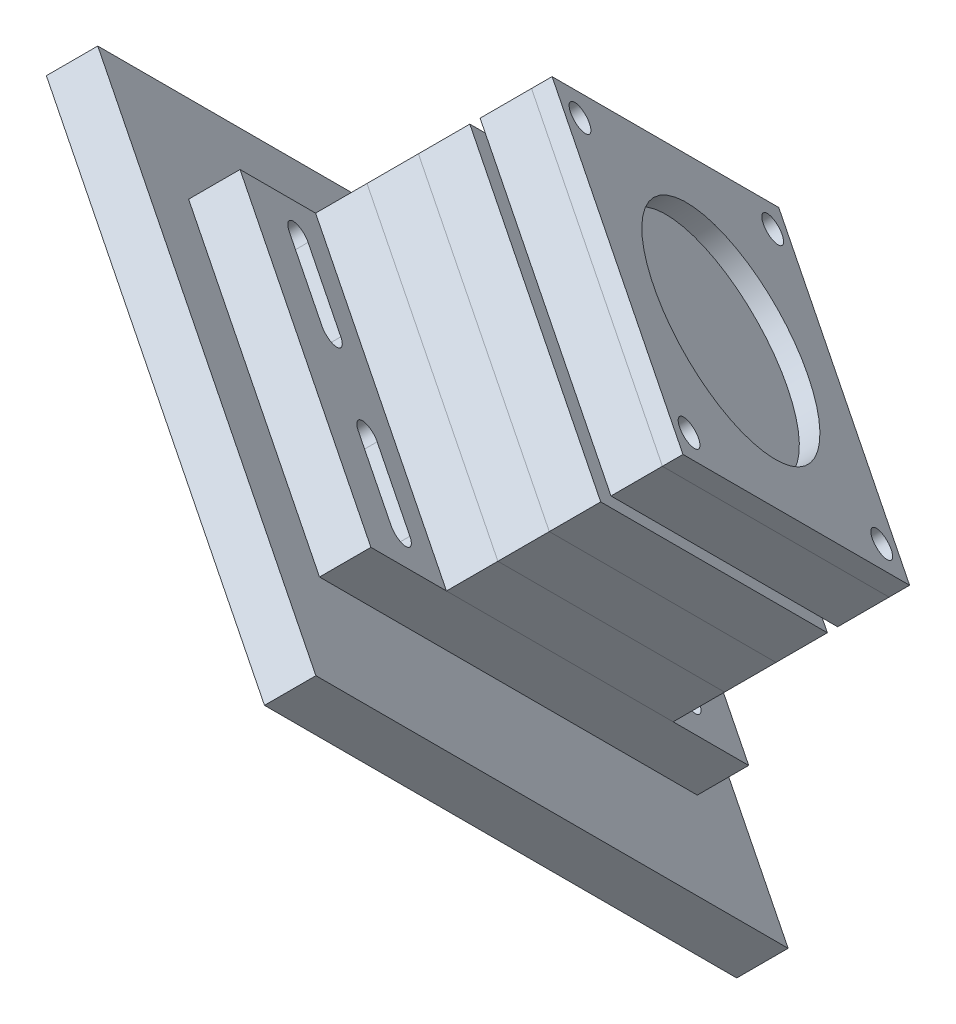
SolidWorks part; units mm, degrees
ref_plane "Front Plane" through (0, 0, 0) normal (0, 0, 1) x (1, 0, 0)
ref_plane "Top Plane" through (0, 0, 0) normal (0, 1, 0) x (1, 0, 0)
ref_plane "Right Plane" through (0, 0, 0) normal (1, 0, 0) x (0, 0, -1)
sketch "Sketch1" plane through (0, 0, 0) normal (0, 1, 0) x (1, 0, 0)
  line L1 (0, 0) -> (80, 0)
  line L2 (0, 0) -> (0, 80)
  line L3 (0, 80) -> (80, 80)
  line L4 (80, 0) -> (80, 80)
  dimension "D1" = 80
  dimension "D2" = 80
extrude "Boss-Extrude1" add sketch "Sketch1" along normal blind 80
sketch3d "3DSketch1"
  line L0 (0, 80, 0) -> (80, 0, 0)
  line L1 (80, 0, 0) -> (0, 0, -80)
  line L2 (0, 0, -80) -> (0, 80, 0)
ref_plane "Plane1" through (26.6667, 26.6667, -26.6667) normal (0.5774, 0.5774, -0.5774) x (-0.8165, 0.4082, -0.4082)
sketch "Sketch2" plane through (26.6667, 26.6667, -26.6667) normal (0.5774, 0.5774, -0.5774) x (-0.8165, 0.4082, -0.4082)
  circle A0 centre (0, 0) radius 97.9507
extrude "Cut-Extrude1" cut sketch "Sketch2" along normal through all
sketch "Sketch3" plane through (26.6667, 26.6667, -26.6667) normal (0.5774, 0.5774, -0.5774) x (-0.4082, -0.4082, -0.8165)
  circle A0 centre (0, 0) radius 12.7
  circle A1 centre (0, 0) radius 78.3026
  dimension "D1" = 25.4
extrude "Cut-Extrude2" cut sketch "Sketch3" against normal blind 40
ref_plane "Plane2" through (0, 0, 0) normal (0.5774, 0.5774, -0.5774) x (-0.8165, 0.4082, -0.4082)
ref_plane "Plane3" through (11.547, 11.547, -11.547) normal (0.5774, 0.5774, -0.5774) x (-0.8165, 0.4082, -0.4082)
sketch "Sketch4" plane through (11.547, 11.547, -11.547) normal (0.5774, 0.5774, -0.5774) x (-0.8165, 0.4082, -0.4082)
  circle A0 centre (0, 0) radius 14.1057
extrude "Cut-Extrude3" cut sketch "Sketch4" along normal blind 40
ref_plane "Plane4" through (8.0829, 8.0829, -8.0829) normal (0.5774, 0.5774, -0.5774) x (0.8165, -0.4082, 0.4082)
sketch "Sketch6" plane through (8.0829, 8.0829, -8.0829) normal (0.5774, 0.5774, -0.5774) x (0.8165, -0.4082, 0.4082)
  line L0 (11.8394, -4.5955) -> (-1.9399, -12.551)
  line L1 (11.8394, -4.5955) -> (-1.9399, -12.551)
  line L2 (11.8394, 4.5955) -> (-1.9399, 12.551)
  line L3 (11.8394, 4.5955) -> (-1.9399, 12.551)
  line L4 (-9.8995, -7.9555) -> (-9.8995, 7.9555)
  line L5 (-9.8995, -7.9555) -> (-9.8995, 7.9555)
  line L7 (18, -18) -> (-18, -18)
  line L8 (18, -18) -> (18, 18)
  line L9 (18, 18) -> (-18, 18)
  line L10 (-18, -18) -> (-18, 18)
  line L11 (18, -18) -> (-18, 18) construction
  line L12 (18, 18) -> (-18, -18) construction
  arc A0 (-9.8995, -7.9555) -> (-1.9399, -12.551) centre (0, 0) ccw
  arc A1 (11.8394, -4.5955) -> (11.8394, 4.5955) centre (0, 0) ccw
  arc A2 (-1.9399, 12.551) -> (-9.8995, 7.9555) centre (0, 0) ccw
  arc A3 (-1.9399, 12.551) -> (-9.8995, 7.9555) centre (0, 0) ccw
  arc A4 (11.8394, -4.5955) -> (11.8394, 4.5955) centre (0, 0) ccw
  arc A5 (-9.8995, -7.9555) -> (-1.9399, -12.551) centre (0, 0) ccw
  dimension "D1" = 36
  dimension "D2" = 36
extrude "Boss-Extrude2" add sketch "Sketch6" against normal blind 5 separate body
sketch "Sketch7" plane through (5.1962, 5.1962, -5.1962) normal (-0.5774, -0.5774, 0.5774) x (0.4082, 0.4082, 0.8165)
  line L0 (6.364, 10.9905) -> (6.364, -10.9905)
  line L1 (6.364, 10.9905) -> (6.364, -10.9905)
  line L2 (-12.7, 0.0161) -> (6.336, 11.0066)
  line L3 (-12.7, 0.0161) -> (6.336, 11.0066)
  line L4 (-12.7, -0.0161) -> (6.336, -11.0066)
  line L5 (-12.7, -0.0161) -> (6.336, -11.0066)
  line L10 (6.5885, 24.5885) -> (-24.5885, 6.5885)
  line L11 (-24.5885, 6.5885) -> (-6.5885, -24.5885)
  line L12 (-6.5885, -24.5885) -> (24.5885, -6.5885)
  line L13 (24.5885, -6.5885) -> (6.5885, 24.5885)
  line L14 (6.5885, 24.5885) -> (-24.5885, 6.5885)
  line L15 (-24.5885, 6.5885) -> (-6.5885, -24.5885)
  line L16 (-6.5885, -24.5885) -> (24.5885, -6.5885)
  line L17 (24.5885, -6.5885) -> (6.5885, 24.5885)
  arc A0 (6.336, -11.0066) -> (6.364, -10.9905) centre (0, 0) ccw
  arc A1 (6.364, 10.9905) -> (6.336, 11.0066) centre (0, 0) ccw
  arc A2 (-12.7, 0.0161) -> (-12.7, -0.0161) centre (0, 0) ccw
  arc A3 (-12.7, 0.0161) -> (-12.7, -0.0161) centre (0, 0) ccw
  arc A4 (6.364, 10.9905) -> (6.336, 11.0066) centre (0, 0) ccw
  arc A5 (6.336, -11.0066) -> (6.364, -10.9905) centre (0, 0) ccw
  dimension "D1" = 0
extrude "Boss-Extrude3" add sketch "Sketch7" along normal blind 5 separate body
sketch "Sketch8" plane through (2.3094, 2.3094, -2.3094) normal (-0.5774, -0.5774, 0.5774) x (0.4082, 0.4082, 0.8165)
  line L0 (-5.6569, 0) -> (2.8284, 4.899)
  line L1 (-5.6569, 0) -> (2.8284, 4.899)
  line L2 (2.8284, 4.899) -> (2.8284, -4.899)
  line L3 (2.8284, 4.899) -> (2.8284, -4.899)
  line L4 (-5.6569, 0) -> (2.8284, -4.899)
  line L5 (-5.6569, 0) -> (2.8284, -4.899)
  line L10 (24.5885, -6.5885) -> (6.5885, 24.5885)
  line L11 (6.5885, 24.5885) -> (-24.5885, 6.5885)
  line L12 (-24.5885, 6.5885) -> (-6.5885, -24.5885)
  line L13 (-6.5885, -24.5885) -> (24.5885, -6.5885)
  line L14 (24.5885, -6.5885) -> (6.5885, 24.5885)
  line L15 (6.5885, 24.5885) -> (-24.5885, 6.5885)
  line L16 (-24.5885, 6.5885) -> (-6.5885, -24.5885)
  line L17 (-6.5885, -24.5885) -> (24.5885, -6.5885)
  dimension "D1" = 0
extrude "Boss-Extrude4" add sketch "Sketch8" along normal blind 5 separate body
sketch "Sketch11" plane through (8.0829, 8.0829, -8.0829) normal (0.5774, 0.5774, -0.5774) x (0.8165, -0.4082, 0.4082)
  line L0 (0, 0) -> (0, -7.2839)
  line L1 (0, 0) -> (-4.4153, 0)
  circle A0 centre (-15, -15.3) radius 1.5
  circle A1 centre (15, -15.3) radius 1.5
  circle A2 centre (15, 15.3) radius 1.5
  circle A3 centre (-15, 15.3) radius 1.5
  dimension "D1" = 3
  dimension "D2" = 15
  dimension "D3" = 15.3
sketch "Sketch12" plane through (11.547, 11.547, -11.547) normal (0.5774, 0.5774, -0.5774) x (-0.4082, -0.4082, -0.8165)
  line L4 (24.5885, 6.5885) -> (-6.5885, 24.5885)
  line L5 (-6.5885, 24.5885) -> (-24.5885, -6.5885)
  line L6 (-24.5885, -6.5885) -> (6.5885, -24.5885)
  line L7 (6.5885, -24.5885) -> (24.5885, 6.5885)
  line L8 (24.5885, 6.5885) -> (-6.5885, 24.5885)
  line L9 (-6.5885, 24.5885) -> (-24.5885, -6.5885)
  line L10 (-24.5885, -6.5885) -> (6.5885, -24.5885)
  line L11 (6.5885, -24.5885) -> (24.5885, 6.5885)
  circle A0 centre (0, 0) radius 12.7
  circle A1 centre (20.7502, 5.3404) radius 1.5 construction
  circle A2 centre (-5.7502, 20.6404) radius 1.5 construction
  circle A3 centre (-20.7502, -5.3404) radius 1.5 construction
  circle A4 centre (5.7502, -20.6404) radius 1.5 construction
  circle A5 centre (20.7502, 5.3404) radius 1.5
  circle A6 centre (-5.7502, 20.6404) radius 1.5
  circle A7 centre (-20.7502, -5.3404) radius 1.5
  circle A8 centre (5.7502, -20.6404) radius 1.5
  dimension "D1" = 0
extrude "Boss-Extrude6" add sketch "Sketch12" against normal blind 5 separate body
ref_plane "Plane5" through (-0.5774, -0.5774, 0.5774) normal (-0.5774, -0.5774, 0.5774) x (-0.8165, 0.4082, -0.4082)
sketch "Sketch15" plane through (-0.5774, -0.5774, 0.5774) normal (-0.5774, -0.5774, 0.5774) x (-0.8165, 0.4082, -0.4082)
  line L0 (-14, 24.5) -> (-5, 24.5)
  line L1 (-18, -30) -> (18, -30)
  line L2 (-18, -30) -> (-18, 30)
  line L3 (-18, 30) -> (18, 30)
  line L4 (18, -30) -> (18, 30)
  line L5 (-18, -30) -> (18, 30) construction
  line L6 (-18, 30) -> (0, 0) construction
  line L7 (-14, 21.5) -> (-5, 21.5)
  line L10 (14, 24.5) -> (5, 24.5)
  line L11 (14, 21.5) -> (5, 21.5)
  line L12 (14, -24.5) -> (5, -24.5)
  line L13 (14, -21.5) -> (5, -21.5)
  line L14 (-14, -24.5) -> (-5, -24.5)
  line L15 (-14, -21.5) -> (-5, -21.5)
  line L18 (12.9, -21.5) -> (18, -30) construction
  arc A0 (-14, 24.5) -> (-14, 21.5) centre (-14, 23) ccw
  arc A1 (-5, 21.5) -> (-5, 24.5) centre (-5, 23) ccw
  arc A2 (14, 24.5) -> (14, 21.5) centre (14, 23) cw
  arc A3 (5, 21.5) -> (5, 24.5) centre (5, 23) cw
  arc A4 (14, -24.5) -> (14, -21.5) centre (14, -23) ccw
  arc A5 (5, -21.5) -> (5, -24.5) centre (5, -23) ccw
  arc A6 (-14, -24.5) -> (-14, -21.5) centre (-14, -23) cw
  arc A7 (-5, -21.5) -> (-5, -24.5) centre (-5, -23) cw
  circle A9 centre (15, 15.3) radius 1.5
  circle A10 centre (15, 15.3) radius 1.5
  circle A11 centre (-15, 15.3) radius 1.5
  circle A12 centre (-15, 15.3) radius 1.5
  circle A13 centre (-15, -15.3) radius 1.5
  circle A14 centre (-15, -15.3) radius 1.5
  circle A15 centre (15, -15.3) radius 1.5
  circle A16 centre (15, -15.3) radius 1.5
  point P0 (0, 0)
  dimension "D5" = 3
  dimension "D6" = 3
  dimension "D1" = 36
  dimension "D2" = 60
  dimension "D3" = 4
  dimension "D4" = 7
  dimension "D7" = 7
  dimension "D8" = 9
  dimension "D9" = 0
  dimension "D10" = 0
  dimension "D11" = 0
  dimension "D12" = 0
extrude "Boss-Extrude8" add sketch "Sketch15" along normal blind 5 separate body
ref_plane "Plane6" through (-3.4641, -3.4641, 3.4641) normal (-0.5774, -0.5774, 0.5774) x (-0.8165, 0.4082, -0.4082)
sketch "Sketch16" plane through (-3.4641, -3.4641, 3.4641) normal (-0.5774, -0.5774, 0.5774) x (-0.8165, 0.4082, -0.4082)
  line L1 (-30, 37.5) -> (30, 37.5)
  line L2 (-30, 37.5) -> (-30, -37.5)
  line L3 (-30, -37.5) -> (30, -37.5)
  line L4 (30, 37.5) -> (30, -37.5)
  line L5 (-30, 37.5) -> (30, -37.5) construction
  line L6 (-30, -37.5) -> (30, 37.5) construction
  line L10 (-11, 18.5) -> (-11, 27.5)
  line L11 (-8, 27.5) -> (-8, 18.5)
  line L12 (11, 18.5) -> (11, 27.5)
  line L13 (8, 27.5) -> (8, 18.5)
  line L14 (-11, -18.5) -> (-11, -27.5)
  line L15 (-8, -27.5) -> (-8, -18.5)
  line L16 (8, -27.5) -> (8, -18.5)
  line L17 (11, -18.5) -> (11, -27.5)
  arc A0 (-8, 27.5) -> (-11, 27.5) centre (-9.5, 27.5) ccw
  arc A1 (-11, 18.5) -> (-8, 18.5) centre (-9.5, 18.5) ccw
  arc A2 (8, 27.5) -> (11, 27.5) centre (9.5, 27.5) cw
  arc A3 (11, 18.5) -> (8, 18.5) centre (9.5, 18.5) cw
  arc A4 (-8, -27.5) -> (-11, -27.5) centre (-9.5, -27.5) cw
  arc A5 (-11, -18.5) -> (-8, -18.5) centre (-9.5, -18.5) cw
  arc A6 (11, -18.5) -> (8, -18.5) centre (9.5, -18.5) ccw
  arc A7 (8, -27.5) -> (11, -27.5) centre (9.5, -27.5) ccw
  point P0 (0, 0)
  dimension "D4" = 3
  dimension "D6" = 3
  dimension "D1" = 75
  dimension "D2" = 60
extrude "Boss-Extrude9" add sketch "Sketch16" along normal blind 5 separate body
sketch "Sketch18" plane through (24.4949, -12.2474, 12.2474) normal (0.8165, -0.4082, 0.4082) x (0.3651, -0.1826, -0.9129)
  line L0 (-32.8421, 19.0695) -> (25.2526, -28.3647)
  line L1 (-3.7947, -4.6476) -> (-6.957, -8.5206)
  line L2 (22.0904, -32.2376) -> (-36.0044, 15.1965) construction
  point P9 (-6.957, -8.5206)
  point P10 (-3.7947, -4.6476)
sketch "Sketch19" plane through (-6.3509, -6.3509, 6.3509) normal (-0.5774, -0.5774, 0.5774) x (0.4082, 0.4082, 0.8165)
  line L0 (0, 0) -> (15, -25.9808)
  line L1 (0, 0) -> (6.3081, 3.642) construction
  line L2 (0, 0) -> (-2.2077, 3.8238) construction
  line L3 (0, 0) -> (6.3081, 3.642)
  line L4 (0, 0) -> (-2.2077, 3.8238)
  line L5 (-19.976, -40.4006) -> (-17.476, -44.7308)
  line L6 (-47.476, 7.2308) -> (-17.476, -44.7308) construction
  line L7 (-17.476, -44.7308) -> (47.476, -7.2308)
  line L8 (47.476, -7.2308) -> (44.976, -2.9006)
  line L9 (47.476, -7.2308) -> (17.476, 44.7308) construction
  line L10 (44.976, -2.9006) -> (-19.976, -40.4006)
  line L11 (-11.3157, -35.4006) -> (-8.8157, -39.7308)
  line L12 (-27.3779, -21.5801) -> (-32.3779, -12.9199)
  line L13 (17.476, 44.7308) -> (-47.476, 7.2308) construction
  line L14 (-7.4593, -10.0801) -> (-12.4593, -1.4199)
  line L15 (-38.0477, 6.9006) -> (-33.0477, -1.7596)
  line L16 (-18.1292, 18.4006) -> (-13.1292, 9.7404)
  line L17 (-27.3779, -21.5801) -> (-23.0477, -19.0801)
  line L18 (-32.3779, -12.9199) -> (-28.0477, -10.4199)
  line L19 (-37.3779, -4.2596) -> (-33.0477, -1.7596)
  line L20 (-42.3779, 4.4006) -> (-38.0477, 6.9006)
  line L21 (-37.3779, -4.2596) -> (-42.3779, 4.4006)
  line L22 (-28.0477, -10.4199) -> (-23.0477, -19.0801)
  line L23 (-17.4593, 7.2404) -> (-22.4593, 15.9006)
  line L24 (-8.1292, 1.0801) -> (-3.1292, -7.5801)
  line L25 (-21.5215, 0.2763) -> (-29.3157, -4.2237) construction
  line L26 (-22.4593, 15.9006) -> (-18.1292, 18.4006)
  line L27 (-7.4593, -10.0801) -> (-3.1292, -7.5801)
  line L28 (-12.4593, -1.4199) -> (-8.1292, 1.0801)
  line L29 (17.3779, 38.9006) -> (13.0477, 36.4006)
  line L30 (13.0477, 36.4006) -> (18.0477, 27.7404)
  line L31 (22.3779, 30.2404) -> (17.3779, 38.9006)
  line L32 (22.3779, 30.2404) -> (18.0477, 27.7404)
  line L33 (27.3779, 21.5801) -> (23.0477, 19.0801)
  line L34 (32.3779, 12.9199) -> (27.3779, 21.5801)
  line L35 (23.0477, 19.0801) -> (28.0477, 10.4199)
  line L36 (32.3779, 12.9199) -> (28.0477, 10.4199)
  line L37 (12.4593, 1.4199) -> (8.1292, -1.0801)
  line L38 (12.4593, 1.4199) -> (7.4593, 10.0801)
  line L39 (3.1292, 7.5801) -> (8.1292, -1.0801)
  line L40 (7.4593, 10.0801) -> (3.1292, 7.5801)
  line L41 (2.4593, 18.7404) -> (-1.8708, 16.2404)
  line L42 (-2.5407, 27.4006) -> (-6.8708, 24.9006)
  line L43 (2.4593, 18.7404) -> (-2.5407, 27.4006)
  line L44 (-6.8708, 24.9006) -> (-1.8708, 16.2404)
  line L45 (-17.4593, 7.2404) -> (-13.1292, 9.7404)
  line L46 (-27.8157, -6.8218) -> (-20.0215, -2.3218) construction
  line L47 (-12.0215, -16.1782) -> (-19.8157, -20.6782) construction
  line L48 (-18.3157, -23.2763) -> (-10.5215, -18.7763) construction
  line L49 (-21.5215, 0.2763) -> (-29.3157, -4.2237)
  line L50 (-27.8157, -6.8218) -> (-20.0215, -2.3218)
  line L51 (-12.0215, -16.1782) -> (-19.8157, -20.6782)
  line L52 (-18.3157, -23.2763) -> (-10.5215, -18.7763)
  line L53 (18.3157, 23.2763) -> (10.5215, 18.7763) construction
  line L54 (12.0215, 16.1782) -> (19.8157, 20.6782) construction
  line L55 (27.8157, 6.8218) -> (20.0215, 2.3218) construction
  line L56 (21.5215, -0.2763) -> (29.3157, 4.2237) construction
  line L57 (18.3157, 23.2763) -> (10.5215, 18.7763)
  line L58 (12.0215, 16.1782) -> (19.8157, 20.6782)
  line L59 (27.8157, 6.8218) -> (20.0215, 2.3218)
  line L60 (21.5215, -0.2763) -> (29.3157, 4.2237)
  line L61 (1.6747, -27.9006) -> (4.1747, -32.2308)
  line L62 (36.3157, -7.9006) -> (38.8157, -12.2308)
  line L63 (23.3253, -15.4006) -> (25.8253, -19.7308)
  line L64 (-47.476, 7.2308) -> (-19.976, -40.4006)
  line L65 (-47.476, 7.2308) -> (17.476, 44.7308)
  line L66 (17.476, 44.7308) -> (44.976, -2.9006)
  arc A0 (-29.3157, -4.2237) -> (-27.8157, -6.8218) centre (-28.5657, -5.5228) ccw construction
  circle A1 centre (-20.7502, 5.3404) radius 1.5
  circle A2 centre (-20.7502, 5.3404) radius 1.5
  circle A3 centre (-5.7502, -20.6404) radius 1.5
  circle A4 centre (-5.7502, -20.6404) radius 1.5
  circle A5 centre (20.7502, -5.3404) radius 1.5
  circle A6 centre (20.7502, -5.3404) radius 1.5
  circle A7 centre (5.7502, 20.6404) radius 1.5
  circle A8 centre (5.7502, 20.6404) radius 1.5
  arc A9 (-20.0215, -2.3218) -> (-21.5215, 0.2763) centre (-20.7715, -1.0228) ccw construction
  arc A10 (-10.5215, -18.7763) -> (-12.0215, -16.1782) centre (-11.2715, -17.4772) ccw construction
  arc A11 (-19.8157, -20.6782) -> (-18.3157, -23.2763) centre (-19.0657, -21.9772) ccw construction
  arc A12 (-29.3157, -4.2237) -> (-27.8157, -6.8218) centre (-28.5657, -5.5228) ccw
  arc A13 (-20.0215, -2.3218) -> (-21.5215, 0.2763) centre (-20.7715, -1.0228) ccw
  arc A14 (-10.5215, -18.7763) -> (-12.0215, -16.1782) centre (-11.2715, -17.4772) ccw
  arc A15 (-19.8157, -20.6782) -> (-18.3157, -23.2763) centre (-19.0657, -21.9772) ccw
  arc A16 (19.8157, 20.6782) -> (18.3157, 23.2763) centre (19.0657, 21.9772) ccw construction
  arc A17 (10.5215, 18.7763) -> (12.0215, 16.1782) centre (11.2715, 17.4772) ccw construction
  arc A18 (29.3157, 4.2237) -> (27.8157, 6.8218) centre (28.5657, 5.5228) ccw construction
  arc A19 (20.0215, 2.3218) -> (21.5215, -0.2763) centre (20.7715, 1.0228) ccw construction
  arc A20 (19.8157, 20.6782) -> (18.3157, 23.2763) centre (19.0657, 21.9772) ccw
  arc A21 (10.5215, 18.7763) -> (12.0215, 16.1782) centre (11.2715, 17.4772) ccw
  arc A22 (29.3157, 4.2237) -> (27.8157, 6.8218) centre (28.5657, 5.5228) ccw
  arc A23 (20.0215, 2.3218) -> (21.5215, -0.2763) centre (20.7715, 1.0228) ccw
  dimension "D1" = 30
  dimension "D6" = 75
  dimension "D7" = 5
  dimension "D8" = 3
  dimension "D9" = 26
  dimension "D10" = 5
  dimension "D11" = 5
  dimension "D12" = 20
  dimension "D13" = 10
  dimension "D14" = 5
  dimension "D15" = 10
  dimension "D16" = 10
  dimension "D17" = 15
  dimension "D2" = 0
  dimension "D3" = 0
  dimension "D4" = 0
  dimension "D5" = 0
sketch "Sketch20" plane through (11.547, 11.547, -11.547) normal (0.5774, 0.5774, -0.5774) x (-0.4082, -0.4082, -0.8165)
  line L4 (6.5885, -24.5885) -> (24.5885, 6.5885)
  line L5 (24.5885, 6.5885) -> (-6.5885, 24.5885)
  line L6 (-6.5885, 24.5885) -> (-24.5885, -6.5885)
  line L7 (-24.5885, -6.5885) -> (6.5885, -24.5885)
  line L8 (6.5885, -24.5885) -> (24.5885, 6.5885)
  line L9 (24.5885, 6.5885) -> (-6.5885, 24.5885)
  line L10 (-6.5885, 24.5885) -> (-24.5885, -6.5885)
  line L11 (-24.5885, -6.5885) -> (6.5885, -24.5885)
  circle A0 centre (0, 0) radius 12.25
  circle A1 centre (20.7502, 5.3404) radius 1.5 construction
  circle A2 centre (-5.7502, 20.6404) radius 1.5 construction
  circle A3 centre (-20.7502, -5.3404) radius 1.5 construction
  circle A4 centre (5.7502, -20.6404) radius 1.5 construction
  circle A5 centre (20.7502, 5.3404) radius 1.5
  circle A6 centre (-5.7502, 20.6404) radius 1.5
  circle A7 centre (-20.7502, -5.3404) radius 1.5
  circle A8 centre (5.7502, -20.6404) radius 1.5
  dimension "D2" = 24.5
  dimension "D1" = 0
extrude "Boss-Extrude10" add sketch "Sketch20" along normal blind 2 separate body
